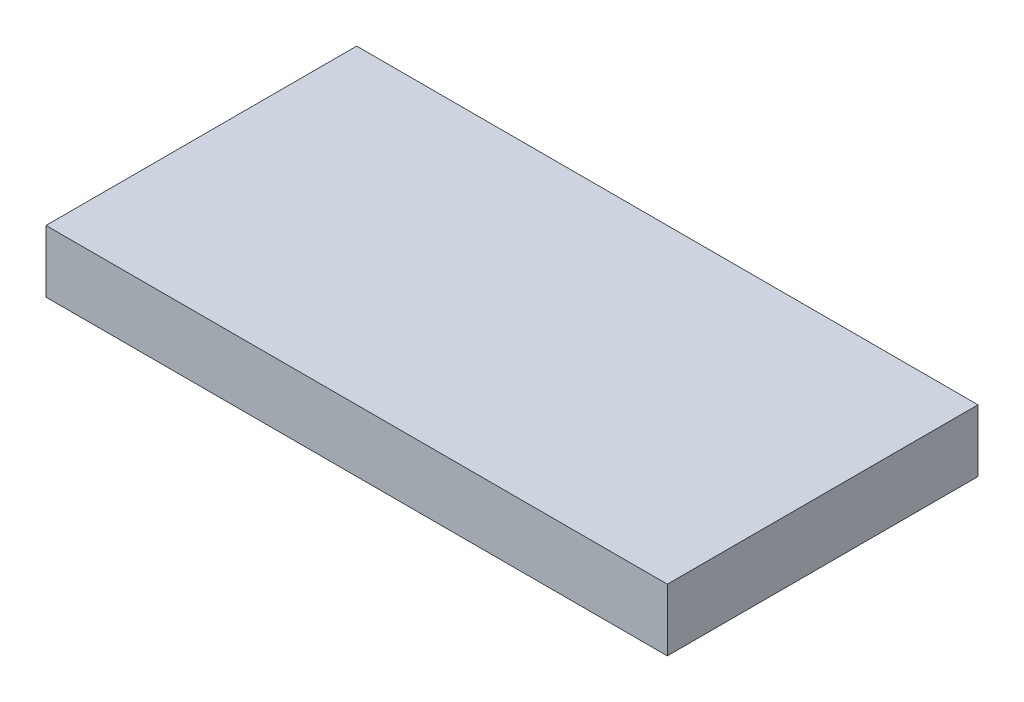
SolidWorks part; units mm, degrees
ref_plane "Front Plane" through (0, 0, 0) normal (0, 0, 1) x (1, 0, 0)
ref_plane "Top Plane" through (0, 0, 0) normal (0, 1, 0) x (1, 0, 0)
ref_plane "Right Plane" through (0, 0, 0) normal (1, 0, 0) x (0, 0, -1)
sketch "Sketch1" plane through (0, 0, 0) normal (0, 1, 0) x (1, 0, 0)
  line L1 (0, 0) -> (40, 0)
  line L2 (0, 0) -> (0, 20)
  line L3 (0, 20) -> (40, 20)
  line L4 (40, 0) -> (40, 20)
extrude "Boss-Extrude1" add sketch "Sketch1" against normal blind 4
